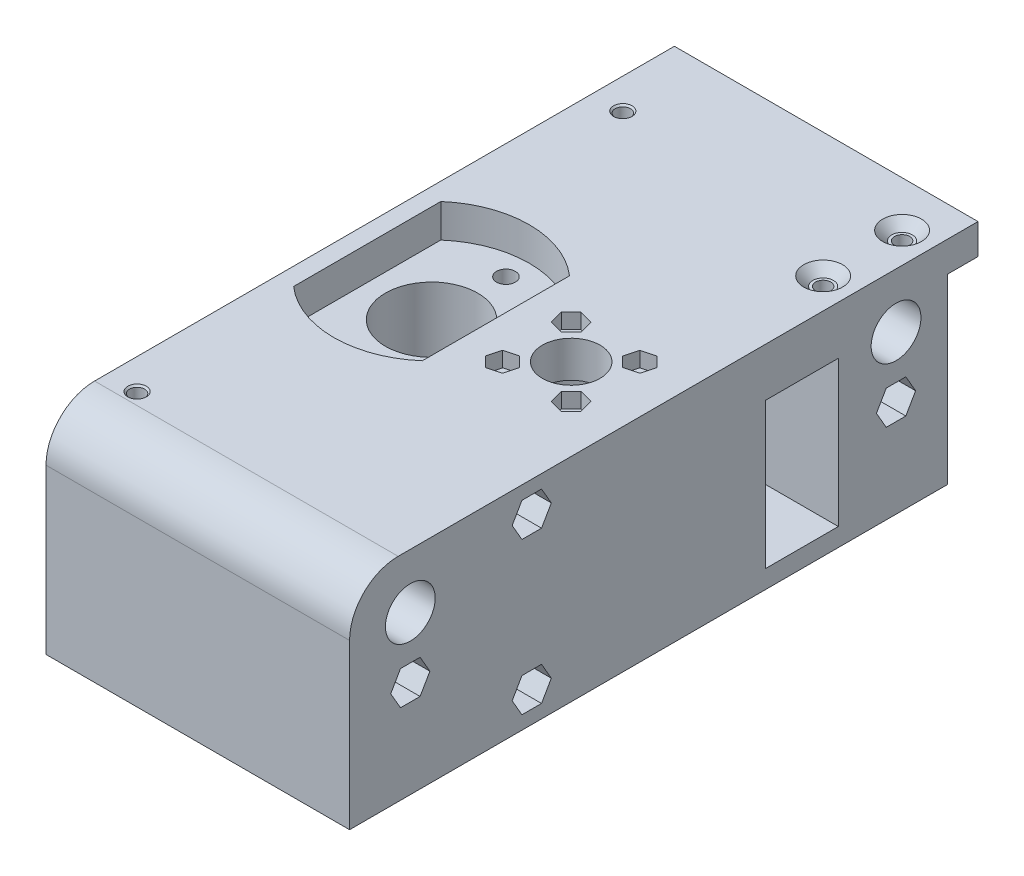
SolidWorks part; units mm, degrees
ref_plane "Front Plane" through (0, 0, 0) normal (0, 0, 1) x (1, 0, 0)
ref_plane "Top Plane" through (0, 0, 0) normal (0, 1, 0) x (1, 0, 0)
ref_plane "Right Plane" through (0, 0, 0) normal (1, 0, 0) x (0, 0, -1)
sketch "Sketch1" plane through (0, 0, 0) normal (1, 0, 0) x (0, 0, -1)
  line L9 (0, 30) -> (0, 0)
  line L10 (0, 0) -> (-98.5, 0)
  line L11 (-98.5, 0) -> (-98.5, 35)
  line L12 (-98.5, 35) -> (5, 35)
  line L13 (5, 35) -> (5, 30)
  line L14 (5, 30) -> (0, 30)
  dimension "D1" = 103.5
  dimension "D2" = 98.5
  dimension "D3" = 30
  dimension "D4" = 35
extrude "Boss-Extrude2" add sketch "Sketch1" along normal blind 50
sketch "Sketch2" plane through (50, 0, 0) normal (1, 0, 0) x (0, 0, -1)
  line L0 (-98.5, 35) -> (-98.5, 0) construction
  line L1 (-98.5, 0) -> (0, 0) construction
  line L2 (-88.5, 26) -> (-8.5, 26) construction
  circle A0 centre (-88.5, 26) radius 4.1
  circle A1 centre (-8.5, 26) radius 4.1
  dimension "D1" = 10
  dimension "D2" = 26
  dimension "D3" = 8.2
  dimension "D5" = 8.2
  dimension "D4" = 80
extrude "Cut-Extrude1" cut sketch "Sketch2" against normal blind 50
sketch "Sketch3" plane through (50, 0, 0) normal (1, 0, 0) x (0, 0, -1)
  line L0 (-8.5, 26) -> (-8.5, 11) construction
  line L1 (-98.5, 0) -> (0, 0) construction
  line L2 (-18, 27) -> (-30, 27)
  line L3 (-18, 27) -> (-18, 3)
  line L4 (-18, 3) -> (-30, 3)
  line L5 (-30, 27) -> (-30, 3)
  point P7 (-24, 27)
  dimension "D1" = 15
  dimension "D2" = 12
  dimension "D3" = 24
  dimension "D4" = 15.5
  dimension "D5" = 3
extrude "Cut-Extrude2" cut sketch "Sketch3" against normal blind 50
sketch "Sketch4" plane through (50, 0, 0) normal (1, 0, 0) x (0, 0, -1)
  line L0 (-88.5, 26) -> (-88.5, 16) construction
  line L1 (-8.5, 26) -> (-8.5, 16) construction
  line L2 (-88.5, 26) -> (-68.5, 26) construction
  line L3 (-68.5, 26) -> (-68.5, 5) construction
  line L4 (-98.5, 0) -> (0, 0) construction
  line L5 (-68.5, 26) -> (-68.5, 30) construction
  circle A0 centre (-88.5, 16) radius 1.6
  circle A4 centre (-68.5, 30) radius 1.6
  circle A5 centre (-68.5, 5) radius 1.6
  circle A6 centre (-8.5, 16) radius 1.6
  dimension "D6" = 3.2
  dimension "D7" = 3.2
  dimension "D8" = 3.2
  dimension "D9" = 3.2
  dimension "D1" = 10
  dimension "D2" = 10
  dimension "D3" = 20
  dimension "D4" = 5
  dimension "D5" = 25
extrude "Cut-Extrude3" cut sketch "Sketch4" against normal blind 50
sketch "Sketch5" plane through (50, 0, 0) normal (1, 0, 0) x (0, 0, -1)
  line L0 (-68.5, 30) -> (-63.5, 30) construction
  line L7 (-88.5, 16) -> (-83.5, 16) construction
  line L8 (-65.275, 30) -> (-66.8875, 32.7929)
  line L9 (-66.8875, 32.7929) -> (-70.1125, 32.7929)
  line L10 (-70.1125, 32.7929) -> (-71.725, 30)
  line L11 (-71.725, 30) -> (-70.1125, 27.2071)
  line L12 (-70.1125, 27.2071) -> (-66.8875, 27.2071)
  line L13 (-66.8875, 27.2071) -> (-65.275, 30)
  line L14 (-68.5, 5) -> (-63.5, 5) construction
  line L21 (-85.275, 16) -> (-86.8875, 18.7929)
  line L22 (-86.8875, 18.7929) -> (-90.1125, 18.7929)
  line L23 (-90.1125, 18.7929) -> (-91.725, 16)
  line L24 (-91.725, 16) -> (-90.1125, 13.2071)
  line L25 (-90.1125, 13.2071) -> (-86.8875, 13.2071)
  line L26 (-86.8875, 13.2071) -> (-85.275, 16)
  line L27 (-8.5, 16) -> (-3.5, 16) construction
  line L28 (-65.275, 5) -> (-66.8875, 7.7929)
  line L29 (-66.8875, 7.7929) -> (-70.1125, 7.7929)
  line L30 (-70.1125, 7.7929) -> (-71.725, 5)
  line L31 (-71.725, 5) -> (-70.1125, 2.2071)
  line L32 (-70.1125, 2.2071) -> (-66.8875, 2.2071)
  line L33 (-66.8875, 2.2071) -> (-65.275, 5)
  line L35 (-5.275, 16) -> (-6.8875, 18.7929)
  line L36 (-6.8875, 18.7929) -> (-10.1125, 18.7929)
  line L37 (-10.1125, 18.7929) -> (-11.725, 16)
  line L38 (-11.725, 16) -> (-10.1125, 13.2071)
  line L39 (-10.1125, 13.2071) -> (-6.8875, 13.2071)
  line L40 (-6.8875, 13.2071) -> (-5.275, 16)
  circle A0 centre (-68.5, 30) radius 3.225 construction
  circle A1 centre (-88.5, 16) radius 3.225 construction
  circle A2 centre (-68.5, 5) radius 3.225 construction
  circle A3 centre (-8.5, 16) radius 3.225 construction
  dimension "D1" = 5
  dimension "D2" = 6.45
  dimension "D5" = 6.45
  dimension "D8" = 6.45
  dimension "D11" = 6.45
  dimension "D3" = 2.7929
  dimension "D4" = 5
  dimension "D6" = 2.7929
  dimension "D7" = 5
  dimension "D9" = 2.7929
  dimension "D10" = 5
  dimension "D12" = 2.7929
extrude "Cut-Extrude4" cut sketch "Sketch5" against normal blind 35
sketch "Sketch6" plane through (0, 35, 0) normal (0, 1, 0) x (1, 0, 0)
  line L0 (50, 5) -> (0, 5) construction
  line L1 (0, 5) -> (0, -98.5) construction
  circle A0 centre (13.5, -48.5) radius 7.6
  dimension "D1" = 53.5
  dimension "D2" = 13.5
  dimension "D3" = 15.2
extrude "Cut-Extrude5" cut sketch "Sketch6" against normal blind 35
sketch "Sketch7" plane through (0, 35, 0) normal (0, 1, 0) x (1, 0, 0)
  line L0 (13.5, -48.5) -> (0, -48.5) construction
  line L1 (0, 5) -> (0, -98.5) construction
  line L2 (24.1, -36.3818) -> (24.1, -60.6182)
  line L5 (2.9, -36.3818) -> (2.9, -60.6182)
  line L6 (13.5, -60.1) -> (13.5, -27.9) construction
  line L7 (24.1, -48.5) -> (2.9, -48.5) construction
  arc A0 (2.9, -60.6182) -> (24.1, -60.6182) centre (13.5, -48.5) ccw
  arc A1 (24.1, -36.3818) -> (2.9, -36.3818) centre (13.5, -48.5) ccw
  dimension "D1" = 32.2
  dimension "D2" = 32.2
  dimension "D3" = 21.2
  dimension "D4" = 21.2
  dimension "D5" = 10.6
extrude "Cut-Extrude6" cut sketch "Sketch7" against normal blind 5.5
sketch "Sketch8" plane through (0, 35, 0) normal (0, 1, 0) x (1, 0, 0)
  line L0 (13.5, -48.5) -> (13.5, -36.25) construction
  line L1 (13.5, -36.25) -> (13.5, -60.75) construction
  circle A0 centre (13.5, -36.25) radius 1.55
  circle A1 centre (13.5, -60.75) radius 1.55
  dimension "D3" = 3.1
  dimension "D4" = 3.1
  dimension "D1" = 12.25
  dimension "D2" = 24.5
extrude "Cut-Extrude7" cut sketch "Sketch8" against normal through all
sketch "Sketch9" plane through (0, 0, 0) normal (0, -1, 0) x (1, 0, 0)
  line L0 (13.5, 60.75) -> (18.5, 60.75) construction
  line L1 (13.5, 36.25) -> (18.5, 36.25) construction
  line L3 (16.725, 60.75) -> (15.1125, 63.5429)
  line L4 (15.1125, 63.5429) -> (11.8875, 63.5429)
  line L5 (11.8875, 63.5429) -> (10.275, 60.75)
  line L6 (10.275, 60.75) -> (11.8875, 57.9571)
  line L7 (11.8875, 57.9571) -> (15.1125, 57.9571)
  line L8 (15.1125, 57.9571) -> (16.725, 60.75)
  line L9 (16.725, 36.25) -> (15.1125, 39.0429)
  line L10 (15.1125, 39.0429) -> (11.8875, 39.0429)
  line L11 (11.8875, 39.0429) -> (10.275, 36.25)
  line L12 (10.275, 36.25) -> (11.8875, 33.4571)
  line L13 (11.8875, 33.4571) -> (15.1125, 33.4571)
  line L14 (15.1125, 33.4571) -> (16.725, 36.25)
  circle A0 centre (13.5, 60.75) radius 3.225 construction
  circle A1 centre (13.5, 36.25) radius 3.225 construction
  dimension "D3" = 6.45
  dimension "D5" = 6.45
  dimension "D1" = 5
  dimension "D2" = 5
  dimension "D4" = 2.7929
  dimension "D6" = 2.7929
extrude "Cut-Extrude8" cut sketch "Sketch9" against normal blind 10
sketch "Sketch10" plane through (0, 0, 0) normal (0, -1, 0) x (1, 0, 0)
  line L0 (13.5, 48.5) -> (36.5, 48.5) construction
  circle A0 centre (36.5, 48.5) radius 11
  dimension "D2" = 22
  dimension "D1" = 23
extrude "Cut-Extrude9" cut sketch "Sketch10" against normal blind 29
sketch "Sketch11" plane through (0, 0, 0) normal (0, -1, 0) x (1, 0, 0)
  line L0 (36.5, 56.5) -> (36.5, 40.5) construction
  line L1 (36.5, 48.5) -> (30.8431, 54.1569) construction
  line L2 (36.5, 48.5) -> (30.8431, 42.8431) construction
  line L3 (36.5, 48.5) -> (42.1569, 42.8431) construction
  line L4 (36.5, 48.5) -> (42.1569, 54.1569) construction
  circle A0 centre (36.5, 48.5) radius 8
  circle A1 centre (30.8431, 54.1569) radius 1.05
  circle A2 centre (42.1569, 54.1569) radius 1.05
  circle A3 centre (30.8431, 42.8431) radius 1.05
  circle A4 centre (42.1569, 42.8431) radius 1.05
  circle A5 centre (36.5, 48.5) radius 4.75
  dimension "D1" = 16
  dimension "D6" = 2.1
  dimension "D7" = 2.1
  dimension "D8" = 2.1
  dimension "D9" = 2.1
  dimension "D10" = 9.5
  dimension "D2" = 45
  dimension "D3" = 45
  dimension "D4" = 90
  dimension "D5" = 45
extrude "Cut-Extrude10" cut sketch "Sketch11" against normal through all contours A1 | A2 | A3 | A4 | A5
sketch "Sketch12" plane through (0, 35, 0) normal (0, 1, 0) x (1, 0, 0)
  line L0 (42.1569, -42.8431) -> (47.1569, -42.8431) construction
  line L1 (42.1569, -54.1569) -> (47.1569, -54.1569) construction
  line L2 (30.8431, -54.1569) -> (35.8431, -54.1569) construction
  line L3 (30.8431, -42.8431) -> (35.8431, -42.8431) construction
  line L4 (30.8431, -54.1569) -> (33.0744, -53.559) construction
  line L5 (44.3881, -42.2453) -> (42.7547, -40.6119)
  line L6 (42.7547, -40.6119) -> (40.5234, -41.2097)
  line L7 (40.5234, -41.2097) -> (39.9256, -43.441)
  line L8 (39.9256, -43.441) -> (41.559, -45.0744)
  line L9 (41.559, -45.0744) -> (43.7903, -44.4766)
  line L10 (43.7903, -44.4766) -> (44.3881, -42.2453)
  line L11 (44.3881, -54.7547) -> (43.7903, -52.5234)
  line L12 (43.7903, -52.5234) -> (41.559, -51.9256)
  line L13 (41.559, -51.9256) -> (39.9256, -53.559)
  line L14 (39.9256, -53.559) -> (40.5234, -55.7903)
  line L15 (40.5234, -55.7903) -> (42.7547, -56.3881)
  line L16 (42.7547, -56.3881) -> (44.3881, -54.7547)
  line L23 (33.0744, -43.441) -> (32.4766, -41.2097)
  line L24 (32.4766, -41.2097) -> (30.2453, -40.6119)
  line L25 (30.2453, -40.6119) -> (28.6119, -42.2453)
  line L26 (28.6119, -42.2453) -> (29.2097, -44.4766)
  line L27 (29.2097, -44.4766) -> (31.441, -45.0744)
  line L28 (31.441, -45.0744) -> (33.0744, -43.441)
  line L29 (33.0744, -53.559) -> (31.441, -51.9256)
  line L30 (31.441, -51.9256) -> (29.2097, -52.5234)
  line L31 (29.2097, -52.5234) -> (28.6119, -54.7547)
  line L32 (28.6119, -54.7547) -> (30.2453, -56.3881)
  line L33 (30.2453, -56.3881) -> (32.4766, -55.7903)
  line L34 (32.4766, -55.7903) -> (33.0744, -53.559)
  line L35 (43.7903, -52.5234) -> (42.1569, -54.1569) construction
  line L36 (42.1569, -42.8431) -> (42.7547, -40.6119) construction
  line L37 (30.8431, -42.8431) -> (32.4766, -41.2097) construction
  circle A0 centre (42.1569, -42.8431) radius 2.31 construction
  circle A1 centre (42.1569, -54.1569) radius 2.31 construction
  circle A2 centre (30.8431, -54.1569) radius 2.31 construction
  circle A3 centre (30.8431, -42.8431) radius 2.31 construction
  dimension "D5" = 4.62
  dimension "D7" = 4.62
  dimension "D9" = 4.62
  dimension "D11" = 4.62
  dimension "D1" = 5
  dimension "D2" = 5
  dimension "D3" = 5
  dimension "D4" = 5
  dimension "D6" = 75
  dimension "D8" = 45
  dimension "D10" = 15
  dimension "D12" = 45
extrude "Cut-Extrude11" cut sketch "Sketch12" against normal blind 2.5
fillet "Fillet1" radius 8 1 edges at (25, 35, 98.5)
sketch "Sketch13" plane through (0, 35, 0) normal (0, 1, 0) x (1, 0, 0)
  line L0 (5, -8.5) -> (5, -88.5) construction
  line L1 (50, 5) -> (0, 5) construction
  line L2 (0, 5) -> (0, -90.5) construction
  dimension "D1" = 80
  dimension "D2" = 13.5
  dimension "D3" = 5
hole_wizard "M3 Tapped Hole3" positions "3DSketch2" profile "Sketch14" tap size "M3" standard "DIN"
sketch3d "3DSketch2"
  point P0 (5, 35, 8.5)
  point P3 (5, 35, 88.5)
sketch "Sketch14" plane through (5, 35, 8.5) normal (1, 0, 0) x (0, 0, 1)
  line L0 (0, 0) -> (0, 9.2511)
  line L1 (0, 9.2511) -> (1.25, 8.5)
  line L2 (1.25, 8.5) -> (1.25, 0.275)
  line L3 (1.25, 0.275) -> (1.525, 0)
  line L5 (1.525, 0) -> (0, 0)
  line L6 (-1.25, 0.275) -> (-1.525, 0) construction
  line L10 (0, 9.2511) -> (-1.25, 8.5) construction
  line L11 (0, -6.35) -> (0, 107.95) construction
  dimension "Tap Drill Dia." = 2.5
  dimension "Tap Drill Depth" = 8.5
  dimension "Near C'Sink Dia." = 3.05
  dimension "Near C'Sink Angle" = 90
  dimension "Drill Angle" = 118
cosmetic thread "Hole Thread1" parameters "D1"=5.0952, "D2"=3
cosmetic thread "Hole Thread2" parameters "D1"=5.0952, "D2"=3
sketch "Sketch15" plane through (0, 35, 0) normal (0, 1, 0) x (1, 0, 0)
  line L0 (45, -2.5) -> (45, -15.5) construction
  line L1 (50, 5) -> (50, -90.5) construction
  line L2 (50, 5) -> (0, 5) construction
  circle A0 centre (45, -2.5) radius 3.2
  circle A1 centre (45, -15.5) radius 3.2
  dimension "D4" = 6.4
  dimension "D5" = 6.4
  dimension "D1" = 13
  dimension "D2" = 5
  dimension "D3" = 7.5
hole_wizard "M3 Tapped Hole4" positions "3DSketch3" profile "Sketch16" tap size "M3" standard "DIN"
sketch3d "3DSketch3"
  point P0 (45, 35, 2.5)
  point P3 (45, 35, 15.5)
sketch "Sketch16" plane through (45, 35, 2.5) normal (1, 0, 0) x (0, 0, 1)
  line L0 (0, 0) -> (0, 7.7511)
  line L1 (0, 7.7511) -> (1.25, 7)
  line L2 (1.25, 7) -> (1.25, 0.275)
  line L3 (1.25, 0.275) -> (1.525, 0)
  line L5 (1.525, 0) -> (0, 0)
  line L6 (-1.25, 0.275) -> (-1.525, 0) construction
  line L10 (0, 7.7511) -> (-1.25, 7) construction
  line L11 (0, -6.35) -> (0, 107.95) construction
  dimension "Tap Drill Dia." = 2.5
  dimension "Tap Drill Depth" = 7
  dimension "Near C'Sink Dia." = 3.05
  dimension "Near C'Sink Angle" = 90
  dimension "Drill Angle" = 118
cosmetic thread "Hole Thread3" parameters "D1"=5.5, "D2"=3
cosmetic thread "Hole Thread4" parameters "D1"=5.5, "D2"=3
extrude "Cut-Extrude12" cut sketch "Sketch15" against normal blind 1.5 draft 45
sketch "Sketch17" plane through (0, 0, 0) normal (0, -1, 0) x (1, 0, 0)
  line L0 (5, 88.5) -> (5, 75.5) construction
  line L1 (50, 98.5) -> (0, 98.5) construction
  line L2 (0, 98.5) -> (0, 0) construction
  circle A0 centre (5, 88.5) radius 3.2
  circle A1 centre (5, 75.5) radius 3.2
  dimension "D4" = 6.4
  dimension "D5" = 6.4
  dimension "D1" = 13
  dimension "D2" = 10
  dimension "D3" = 5
hole_wizard "M3 Tapped Hole5" positions "3DSketch4" profile "Sketch18" tap size "M3" standard "DIN"
sketch3d "3DSketch4"
  point P0 (5, 0, 88.5)
  point P3 (5, 0, 75.5)
sketch "Sketch18" plane through (5, 0, 88.5) normal (1, 0, 0) x (0, 0, -1)
  line L0 (0, 0) -> (0, 7.7511)
  line L1 (0, 7.7511) -> (1.25, 7)
  line L2 (1.25, 7) -> (1.25, 0.275)
  line L3 (1.25, 0.275) -> (1.525, 0)
  line L5 (1.525, 0) -> (0, 0)
  line L6 (-1.25, 0.275) -> (-1.525, 0) construction
  line L10 (0, 7.7511) -> (-1.25, 7) construction
  line L11 (0, -6.35) -> (0, 107.95) construction
  dimension "Tap Drill Dia." = 2.5
  dimension "Tap Drill Depth" = 7
  dimension "Near C'Sink Dia." = 3.05
  dimension "Near C'Sink Angle" = 90
  dimension "Drill Angle" = 118
cosmetic thread "Hole Thread5" parameters "D1"=5.5, "D2"=3
cosmetic thread "Hole Thread6" parameters "D1"=5.5, "D2"=3
extrude "Cut-Extrude13" cut sketch "Sketch17" against normal blind 1.5 draft 45
